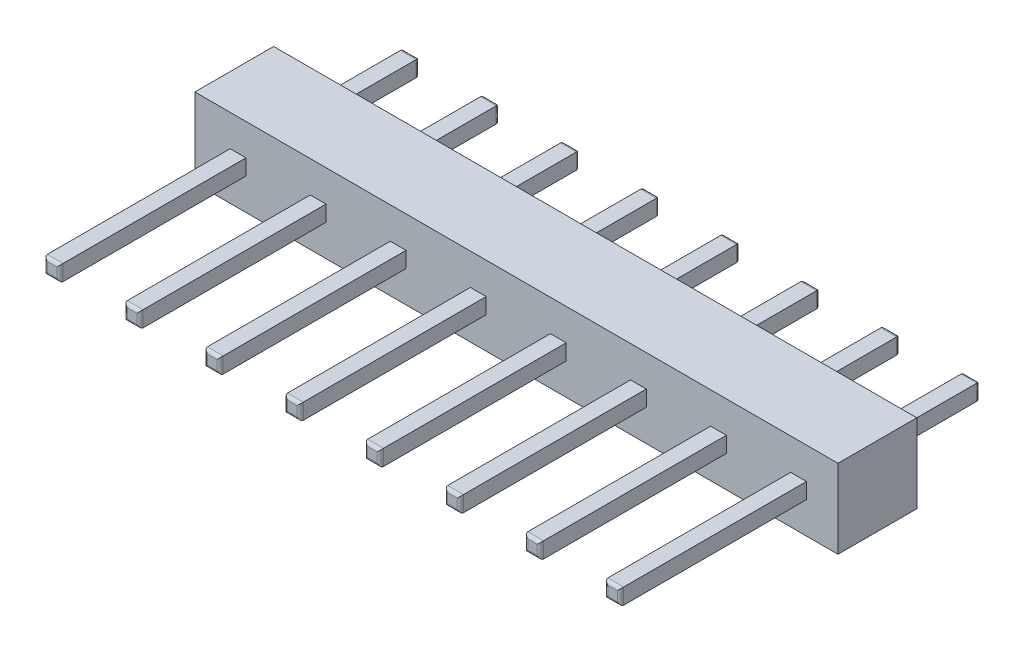
SolidWorks part; units mm, degrees
ref_plane "Front Plane" through (0, 0, 0) normal (0, 0, 1) x (1, 0, 0)
ref_plane "Top Plane" through (0, 0, 0) normal (0, 1, 0) x (1, 0, 0)
ref_plane "Right Plane" through (0, 0, 0) normal (1, 0, 0) x (0, 0, -1)
sketch "Sketch1" plane through (0, 0, 0) normal (0, 0, 1) x (1, 0, 0)
  line L1 (-10.2, 1.25) -> (10.2, 1.25)
  line L2 (-10.2, 1.25) -> (-10.2, -1.25)
  line L3 (-10.2, -1.25) -> (10.2, -1.25)
  line L4 (10.2, 1.25) -> (10.2, -1.25)
  line L5 (-10.2, 1.25) -> (10.2, -1.25) construction
  line L6 (-10.2, -1.25) -> (10.2, 1.25) construction
  point P0 (0, 0)
  dimension "D1" = 2.5
  dimension "D2" = 20.4
extrude "Boss-Extrude1" add sketch "Sketch1" along normal blind 2.5
sketch "Sketch2" plane through (0, 0, 2.5) normal (0, 0, 1) x (1, 0, 0)
  line L0 (10.2, 1.25) -> (7.7, 1.25) construction
  line L1 (10.2, 1.25) -> (-10.2, 1.25) construction
  line L2 (7.7, 1.25) -> (7.7, -1.25) construction
  line L3 (-10.2, -1.25) -> (10.2, -1.25) construction
  line L4 (8.95, 1.25) -> (8.95, 0) construction
  line L5 (8.95, 0) -> (7.7, 0) construction
  line L7 (8.7, 0.25) -> (9.2, 0.25)
  line L8 (8.7, 0.25) -> (8.7, -0.25)
  line L9 (8.7, -0.25) -> (9.2, -0.25)
  line L10 (9.2, 0.25) -> (9.2, -0.25)
  line L11 (8.7, 0.25) -> (9.2, -0.25) construction
  line L12 (8.7, -0.25) -> (9.2, 0.25) construction
  dimension "D1" = 2.5
  dimension "D2" = 0.5
  dimension "D3" = 0.5
extrude "Boss-Extrude2" add sketch "Sketch2" along normal blind 5.9
fillet "Fillet1" radius 0.1 4 edges at (9.2, 0, 8.4) (8.95, 0.25, 8.4) (8.7, 0, 8.4) (8.95, -0.25, 8.4)
pattern_linear "LPattern1" count 8 spacing 2.54 along (-1, 0, 0) of "Fillet1", "Boss-Extrude2"
sketch "Sketch4" plane through (0, 0, 0) normal (0, 0, -1) x (-1, 0, 0)
  line L0 (-8.7, 0.25) -> (-8.7, -0.25) construction
  line L1 (-8.7, -0.25) -> (-9.2, -0.25) construction
  line L2 (-9.2, 0.25) -> (-8.7, 0.25) construction
  line L3 (-9.2, -0.25) -> (-9.2, 0.25) construction
  line L4 (-8.7, 0.25) -> (-8.7, -0.25)
  line L5 (-8.7, -0.25) -> (-9.2, -0.25)
  line L6 (-9.2, 0.25) -> (-8.7, 0.25)
  line L7 (-9.2, -0.25) -> (-9.2, 0.25)
extrude "Boss-Extrude3" add sketch "Sketch4" along normal blind 3
fillet "Fillet2" radius 0.1 4 edges at (8.7, 0, -3) (8.95, -0.25, -3) (8.95, 0.25, -3) (9.2, 0, -3)
pattern_linear "LPattern2" count 8 spacing 2.54 along (-1, 0, 0) of "Fillet2", "Boss-Extrude3"
